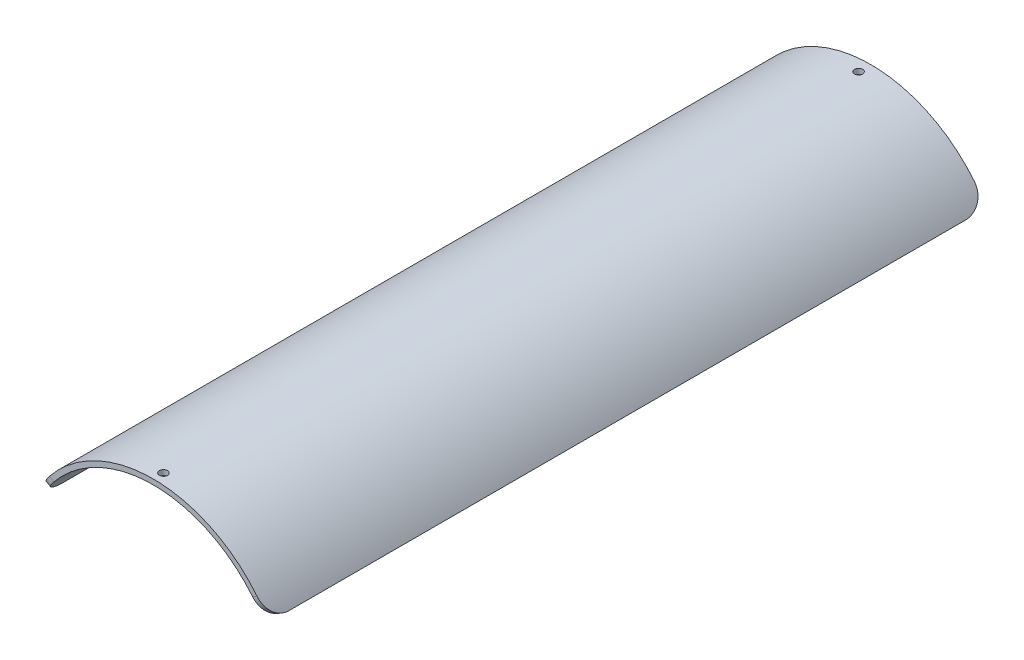
SolidWorks part; units mm, degrees
material "E-Glass Fiber"
ref_plane "Ön Düzlem" through (0, 0, 0) normal (0, 0, 1) x (1, 0, 0)
ref_plane "Üst Düzlem" through (0, 0, 0) normal (0, 1, 0) x (1, 0, 0)
ref_plane "Sağ Düzlem" through (0, 0, 0) normal (1, 0, 0) x (0, 0, -1)
sketch "Sketch1" plane through (0, 0, 0) normal (0, 0, 1) x (1, 0, 0)
  line L0 (0, -65) -> (0, 65) construction
  line L1 (0, 0) -> (56.2917, 32.5) construction
  line L2 (0, 0) -> (-56.2917, 32.5) construction
  line L3 (-56.2917, 32.5) -> (-54.1266, 31.25)
  line L4 (56.2917, 32.5) -> (54.1266, 31.25)
  circle A0 centre (0, 0) radius 65 construction
  arc A1 (-56.2917, 32.5) -> (56.2917, 32.5) centre (0, 0) cw
  arc A2 (-54.1266, 31.25) -> (54.1266, 31.25) centre (0, 0) cw
  circle A3 centre (0, 0) radius 62.5 construction
  dimension "D3" = 130
  dimension "D4" = 125
  dimension "D1" = 120
  dimension "D2" = 60
extrude "Boss-Extrude1" add sketch "Sketch1" along normal mid plane 350
fillet "Fillet1" radius 10 4 edges at (-55.2091, 31.875, -175) (55.2091, 31.875, -175) (55.2091, 31.875, 175) (-55.2091, 31.875, 175)
sketch "Sketch3" plane through (0, 0, 0) normal (0, 1, 0) x (1, 0, 0)
  line L0 (-56.2917, 175) -> (-56.2917, -175) construction
  line L1 (0, 175) -> (0, 169) construction
  line L2 (56.2917, -175) -> (-56.2917, -175) construction
  line L3 (0, 169) -> (0, -170) construction
  line L4 (56.2917, 175) -> (-56.2917, 175) construction
  line L5 (0, -170) -> (0, -175) construction
  line L6 (56.2917, 175) -> (56.2917, -175) construction
  line L7 (-50.6215, -175) -> (50.6215, -175) construction
  circle A0 centre (0, -170) radius 2
  circle A1 centre (0, 169) radius 2
  point P3 (-56.2917, 0)
  point P6 (0, -175)
  point P9 (0, 175)
  point P12 (56.2917, 0)
  point P14 (0, 0)
  dimension "D1" = 350
  dimension "D3" = 5
  dimension "D4" = 6
extrude "Cut-Extrude1" cut sketch "Sketch3" along normal blind 340
